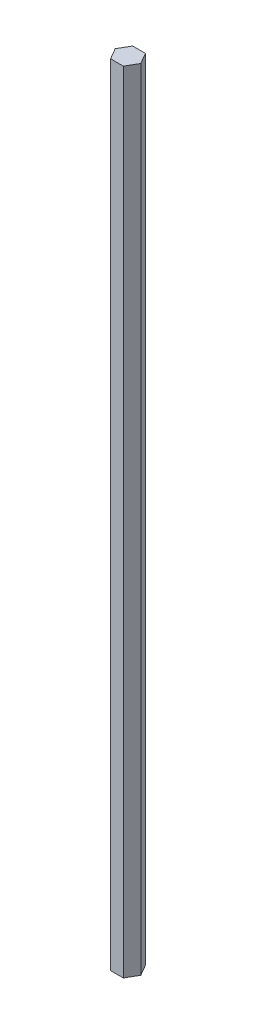
SolidWorks part; units mm, degrees
material "201 退火不锈钢 (SS)"
ref_plane "前视基准面" through (0, 0, 0) normal (0, 0, 1) x (1, 0, 0)
ref_plane "上视基准面" through (0, 0, 0) normal (0, 1, 0) x (1, 0, 0)
ref_plane "右视基准面" through (0, 0, 0) normal (1, 0, 0) x (0, 0, -1)
sketch "草图1" plane through (0, 0, 0) normal (0, 1, 0) x (1, 0, 0)
  line L1 (4.0415, 0) -> (2.0207, 3.5)
  line L2 (2.0207, 3.5) -> (-2.0207, 3.5)
  line L3 (-2.0207, 3.5) -> (-4.0415, 0)
  line L4 (-4.0415, 0) -> (-2.0207, -3.5)
  line L5 (-2.0207, -3.5) -> (2.0207, -3.5)
  line L6 (2.0207, -3.5) -> (4.0415, 0)
  circle A0 centre (0, 0) radius 3.5 construction
  dimension "D1" = 7
extrude "凸台-拉伸1" add sketch "草图1" along normal blind 250
